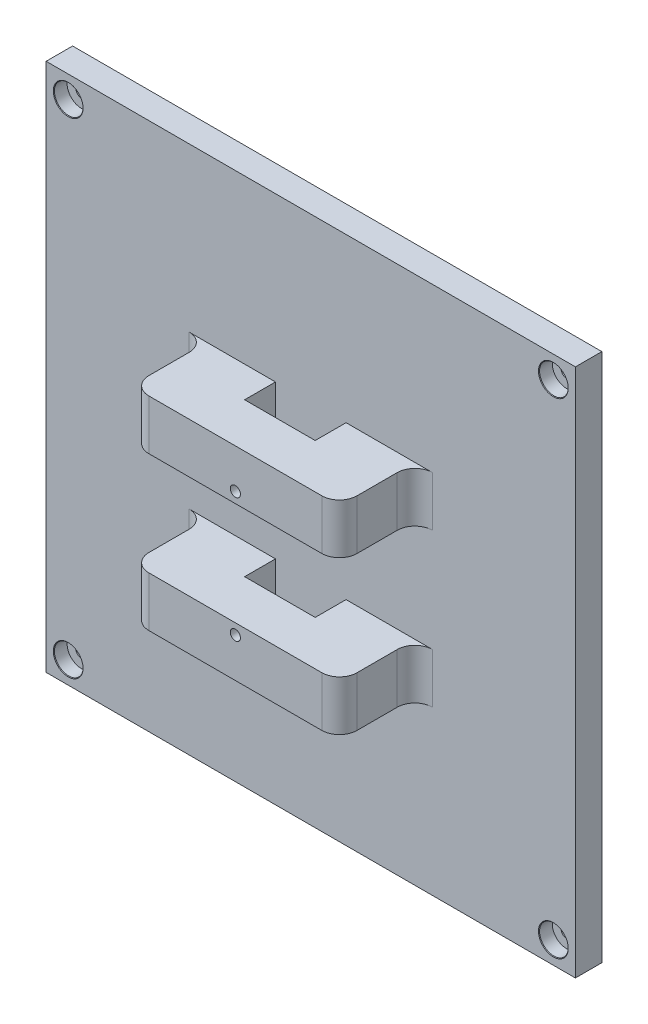
SolidWorks part; units mm, degrees
ref_plane "Front Plane" through (0, 0, 0) normal (1, 0, 0) x (0, 1, 0)
ref_plane "Top Plane" through (0, 0, 0) normal (0, 0, 1) x (0, 1, 0)
ref_plane "Right Plane" through (0, 0, 0) normal (0, 1, 0) x (-1, 0, 0)
sketch "Sketch1" plane through (0, 0, 0) normal (0, 0, 1) x (0, 1, 0)
  line L1 (-60, -60) -> (60, -60)
  line L2 (-60, -60) -> (-60, 60)
  line L3 (-60, 60) -> (60, 60)
  line L4 (60, -60) -> (60, 60)
  line L5 (-60, -60) -> (60, 60) construction
  line L6 (-60, 60) -> (60, -60) construction
  point P0 (0, 0)
  dimension "D1" = 120
  dimension "D2" = 120
extrude "Boss-Extrude1" add sketch "Sketch1" along normal blind 6
sketch "Sketch2" plane through (0, 0, 6) normal (0, 0, 1) x (1, 0, 0)
  line L0 (-60, 60) -> (-50, 60)
  line L1 (-60, 60) -> (-60, 50)
  line L2 (-60, 50) -> (-50, 50)
  line L3 (-50, 60) -> (-50, 50)
  line L4 (45, 60) -> (45, 45)
  line L5 (60, 45) -> (45, 45)
  line L6 (60, 60) -> (60, 45)
  line L7 (60, 60) -> (45, 60)
  line L8 (60, -60) -> (45, -60)
  line L9 (60, -60) -> (60, -45)
  line L10 (60, -45) -> (45, -45)
  line L11 (45, -60) -> (45, -45)
  line L12 (-45, -60) -> (-45, -45)
  line L13 (-60, -45) -> (-45, -45)
  line L14 (-60, -60) -> (-60, -45)
  line L15 (-60, -60) -> (-45, -60)
  circle A0 centre (-55, 55) radius 1.25
  point P28 (-55, 55)
  dimension "D2" = 2.5
  dimension "D4" = 5
  dimension "D1" = 10
  dimension "D3" = 10
  dimension "D5" = 5
hole_wizard "CBORE for M3 SBHCS1" positions "Sketch2" profile "Sketch7" counterbore size "M3" standard "ANSI Metric" end condition through all
sketch "Sketch7" plane through (-55, 55, 6) normal (1, 0, 0) x (0, -1, 0)
  line L0 (0, 0) -> (0, 6)
  line L1 (0, 6) -> (1.25, 6)
  line L3 (1.25, 6) -> (1.25, 3)
  line L4 (3.25, 3) -> (1.25, 3)
  line L5 (3.25, 3) -> (3.25, 0.125)
  line L6 (3.25, 0.125) -> (3.375, 0)
  line L7 (3.375, 0) -> (0, 0)
  line L8 (-3.25, 0.125) -> (-3.375, 0) construction
  line L11 (0, -6.35) -> (0, 107.95) construction
  dimension "Thru Hole Dia." = 2.5
  dimension "Thru Hole Depth" = 6
  dimension "C'Bore Dia." = 6.5
  dimension "C'Bore Depth" = 3
  dimension "Near C'Sink Dia." = 6.75
  dimension "Near C'Sink Angle" = 90
mirror "Mirror2" about plane through (0, 0, 0) normal (1, 0, 0) of "CBORE for M3 SBHCS1" second plane through (0, 0, 0) second plane normal (0, 1, 0)
sketch "Sketch3" plane through (0, 0, 6) normal (0, 0, 1) x (1, 0, 0)
  line L0 (3.3, 0) -> (-3.3, 0) construction
  line L1 (23.598, -23.0365) -> (-23.598, -23.0365)
  line L2 (23.598, -23.0365) -> (23.598, -11.7)
  line L3 (23.598, -11.7) -> (-23.598, -11.7)
  line L4 (-23.598, -23.0365) -> (-23.598, -11.7)
  line L5 (23.598, -23.0365) -> (-23.598, -11.7) construction
  line L6 (23.598, -11.7) -> (-23.598, -23.0365) construction
  line L7 (-23.598, 23.0365) -> (-23.598, 11.7)
  line L8 (23.598, 11.7) -> (-23.598, 11.7)
  line L9 (23.598, 23.0365) -> (23.598, 11.7)
  line L10 (23.598, 23.0365) -> (-23.598, 23.0365)
  point P0 (0, -17.3682)
  dimension "D1" = 11.7
extrude "Boss-Extrude2" add sketch "Sketch3" along normal blind 17.1
sketch "Sketch4" plane through (0, -23.0365, 0) normal (0, -1, 0) x (1, 0, 0)
  line L0 (-8, 6) -> (-8, 13)
  line L1 (-8, 6) -> (8, 6)
  line L2 (-8, 13) -> (8, 13)
  line L3 (8, 6) -> (8, 13)
  line L4 (-60, 6) -> (60, 6) construction
  line L5 (0, -3.3) -> (0, 3.3) construction
  dimension "D1" = 8
  dimension "D2" = 8
  dimension "D3" = 7
extrude "Cut-Extrude3" cut sketch "Sketch4" against normal through all
sketch "Sketch6" plane through (0, 0, 23.1) normal (0, 0, 1) x (1, 0, 0)
  line L0 (0, -3.3) -> (0, 3.3) construction
  line L1 (-23.598, 11.7) -> (23.598, 11.7) construction
  line L2 (3.3, 0) -> (-3.3, 0) construction
  circle A0 centre (0, 14.1) radius 1.15
  circle A1 centre (0, -14.1) radius 1.15
  dimension "D1" = 2.3
  dimension "D2" = 2.4
extrude "Cut-Extrude4" cut sketch "Sketch6" against normal blind 8
fillet "Fillet1" radius 4 8 edges at (-23.598, -17.3682, 6) (-23.598, -17.3682, 23.1) (-23.598, 17.3682, 6) (-23.598, 17.3682, 23.1) (23.598, 17.3682, 6) (23.598, 17.3682, 23.1) (23.598, -17.3682, 6) (23.598, -17.3682, 23.1)
